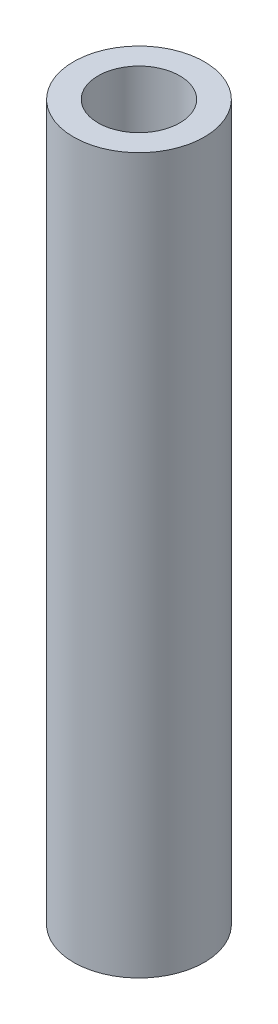
SolidWorks part; units mm, degrees
ref_plane "前视基准面" through (0, 0, 0) normal (0, 0, 1) x (1, 0, 0)
ref_plane "上视基准面" through (0, 0, 0) normal (0, 1, 0) x (1, 0, 0)
ref_plane "右视基准面" through (0, 0, 0) normal (1, 0, 0) x (0, 0, -1)
other "Configuration Table"
sketch "草图1" plane through (0, 0, 0) normal (0, 1, 0) x (1, 0, 0)
  circle A0 centre (0, 0) radius 2.5
  circle A1 centre (0, 0) radius 4
  dimension "D1" = 5
  dimension "D2" = 8
extrude "凸台-拉伸1" add sketch "草图1" along normal blind 43.75
